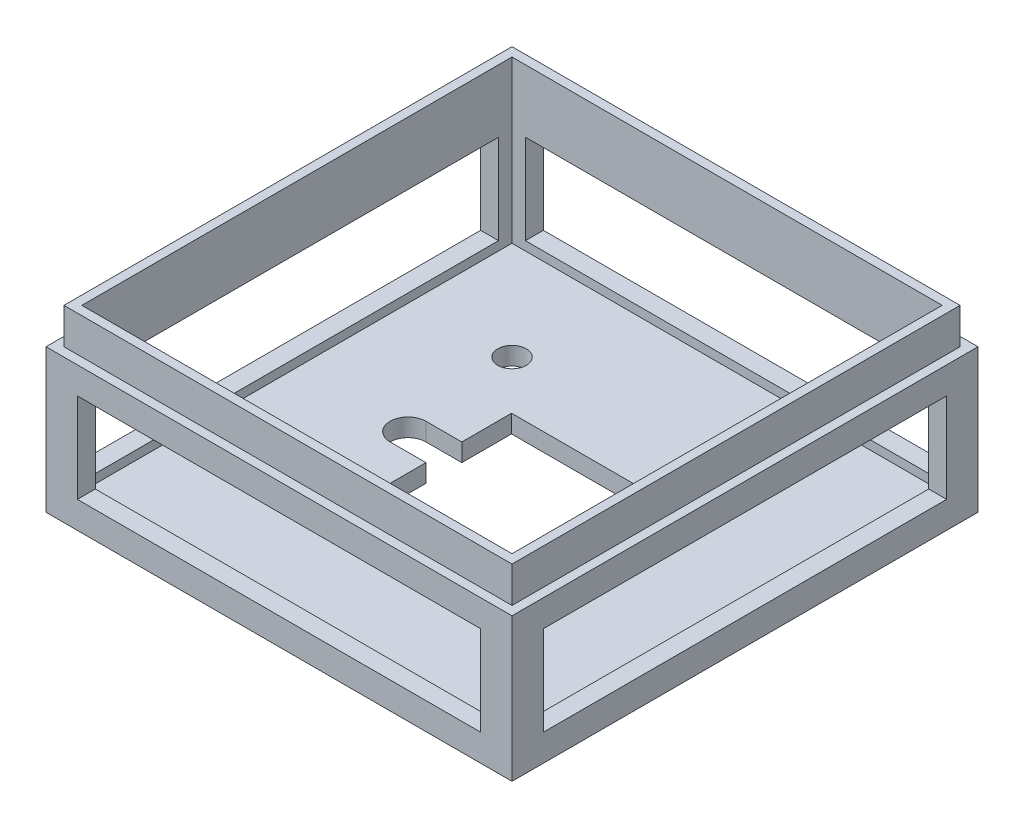
SolidWorks part; units mm, degrees
ref_plane "前视基准面" through (0, 0, 0) normal (0, 0, 1) x (1, 0, 0)
ref_plane "上视基准面" through (0, 0, 0) normal (0, 1, 0) x (1, 0, 0)
ref_plane "右视基准面" through (0, 0, 0) normal (1, 0, 0) x (0, 0, -1)
other "Configuration Table"
sketch "草图1" plane through (0, 0, 0) normal (0, 1, 0) x (1, 0, 0)
  line L0 (-16, 16) -> (-13, 16) construction
  line L1 (-16, -16) -> (16, -16)
  line L2 (-16, -16) -> (-16, 16)
  line L3 (-16, 16) -> (16, 16)
  line L4 (16, -16) -> (16, 16)
  line L5 (-16, -16) -> (16, 16) construction
  line L6 (-16, 16) -> (16, -16) construction
  line L7 (-13, 16) -> (-13, 13) construction
  line L8 (0, 16) -> (0, -49984) construction
  line L9 (-16, 0) -> (49984, 0) construction
  line L10 (-7.6, 0) -> (-11.6, 0)
  line L11 (-7.6, -7.55) -> (7.6, -7.55)
  line L12 (-7.6, -7.55) -> (-7.6, 7.55)
  line L13 (-7.6, 7.55) -> (7.6, 7.55)
  line L14 (7.6, -7.55) -> (7.6, 7.55)
  line L15 (-7.6, -7.55) -> (7.6, 7.55) construction
  line L16 (-7.6, 7.55) -> (7.6, -7.55) construction
  line L17 (-11.6, 2) -> (-7.6, 2)
  line L18 (-11.6, -2) -> (-7.6, -2)
  line L19 (11.6, 2) -> (7.6, 2)
  line L20 (11.6, -2) -> (7.6, -2)
  line L21 (-26, 26) -> (26, 26)
  line L22 (26, -26) -> (26, 26)
  line L23 (-26, -26) -> (26, -26)
  line L24 (-26, -26) -> (-26, 26)
  circle A0 centre (-13, 13) radius 1.6
  circle A1 centre (-11.6, 0) radius 2
  circle A2 centre (11.6, 0) radius 2
  circle A3 centre (13, 13) radius 1.6
  circle A4 centre (13, -13) radius 1.6
  circle A5 centre (-13, -13) radius 1.6
  point P0 (0, 0)
  point P11 (0, 16)
  point P12 (0, -16)
  point P15 (-16, 0)
  point P16 (0, 0)
  dimension "D5" = 3.2
  dimension "D9" = 4
  dimension "D1" = 32
  dimension "D2" = 32
  dimension "D3" = 3
  dimension "D4" = 3
  dimension "D6" = 15.2
  dimension "D7" = 15.1
  dimension "D8" = 4
  dimension "D10" = 10
extrude "凸台-拉伸2" add sketch "草图1" along normal blind 20 contours L24 L23 L22 L21 L4 L1 L2 L3 | L1 L4 L3 L2 A3 A0 L19 A2 L20 L14 L11 L12 L18 A1 L17 L13 A4 A5
shell "抽壳6" thickness 2
sketch "草图3" plane through (0, 20, 0) normal (0, 1, 0) x (1, 0, 0)
  line L0 (-24, 24) -> (-24, -24)
  line L1 (-26, 26) -> (26, 26)
  line L2 (-26, 26) -> (-26, -26)
  line L3 (-26, -26) -> (26, -26)
  line L4 (26, 26) -> (26, -26)
  line L5 (-24, -24) -> (24, -24)
  line L6 (24, 24) -> (24, -24)
  line L7 (-24, 24) -> (24, 24)
  line L8 (-25, 25) -> (25, 25)
  line L9 (25, 25) -> (25, -25)
  line L10 (-25, -25) -> (25, -25)
  line L11 (-25, 25) -> (-25, -25)
  line M2 (-26, 26) -> (-26, -26)
  line M3 (-26, -26) -> (26, -26)
  line M4 (26, -26) -> (26, 26)
  line M5 (26, 26) -> (-26, 26)
  dimension "D1" = 2
  dimension "D2" = 1
extrude "切除-拉伸5" cut sketch "草图3" against normal blind 4 contours L11 L8 L9 L10 M5 M2 M3 M4
sketch "草图4" plane through (0, 0, 26) normal (0, 0, 1) x (1, 0, 0)
  line L0 (0, 0) -> (0, 16) construction
  line L1 (-25, 16) -> (25, 16) construction
  line L2 (-26, 8) -> (26, 8) construction
  line L3 (-26, 16) -> (-26, 0) construction
  line L4 (26, 16) -> (26, 0) construction
  line L6 (22.5, 3) -> (-22.5, 3)
  line L7 (22.5, 3) -> (22.5, 13)
  line L8 (22.5, 13) -> (-22.5, 13)
  line L9 (-22.5, 3) -> (-22.5, 13)
  line L10 (22.5, 3) -> (-22.5, 13) construction
  line L11 (22.5, 13) -> (-22.5, 3) construction
  point P11 (0, 8)
  dimension "D1" = 45
  dimension "D2" = 10
extrude "切除-拉伸6" cut sketch "草图4" against normal through all
sketch "草图5" plane through (-26, 0, 0) normal (-1, 0, 0) x (0, 0, 1)
  line L0 (0, 16) -> (0, 0)
  line L1 (-26, 16) -> (26, 16) construction
  line L2 (-26, 8) -> (26, 8)
  line L3 (-26, 16) -> (-26, 0) construction
  line L4 (26, 16) -> (26, 0) construction
  line L6 (22.5, 3) -> (-22.5, 3)
  line L7 (22.5, 3) -> (22.5, 13)
  line L8 (22.5, 13) -> (-22.5, 13)
  line L9 (-22.5, 3) -> (-22.5, 13)
  line L10 (22.5, 3) -> (-22.5, 13) construction
  line L11 (22.5, 13) -> (-22.5, 3) construction
  point P11 (0, 8)
  dimension "D1" = 45
  dimension "D2" = 10
extrude "切除-拉伸7" cut sketch "草图5" against normal through all contours L9 L2 L0 L8 | L7 L8 L0 L2 | L6 L7 L2 L0 | L9 L6 L0 L2
